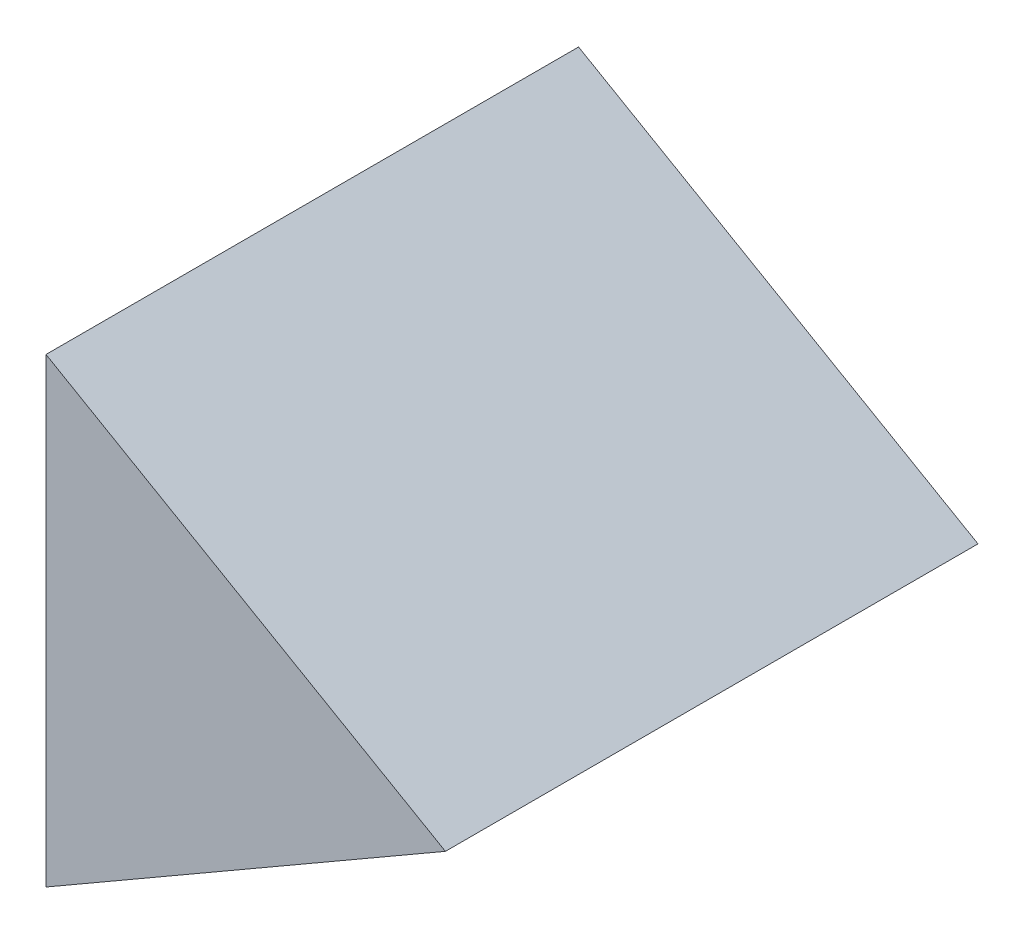
SolidWorks part; units mm, degrees
ref_plane "前视基准面" through (0, 0, 0) normal (0, 0, 1) x (1, 0, 0)
ref_plane "上视基准面" through (0, 0, 0) normal (0, 1, 0) x (1, 0, 0)
ref_plane "右视基准面" through (0, 0, 0) normal (1, 0, 0) x (0, 0, -1)
other "Configuration Table"
sketch "草图1" plane through (0, 0, 0) normal (0, 0, 1) x (1, 0, 0)
  line L1 (500, 0) -> (-250, 433.0127)
  line L2 (-250, 433.0127) -> (-250, -433.0127)
  line L3 (-250, -433.0127) -> (500, 0)
  circle A0 centre (0, 0) radius 250 construction
extrude "凸台-拉伸1" add sketch "草图1" along normal blind 1000
sketch "草图2" plane through (0, 0, 0) normal (0, 0, 1) x (1, 0, 0)
  line L1 (500, 0) -> (-250, 433.0127)
  line L2 (-250, 433.0127) -> (-250, -433.0127)
  line L3 (-250, -433.0127) -> (500, 0)
  circle A0 centre (0, 0) radius 250 construction
extrude "凸台-拉伸2" add sketch "草图2" along normal blind 1000
